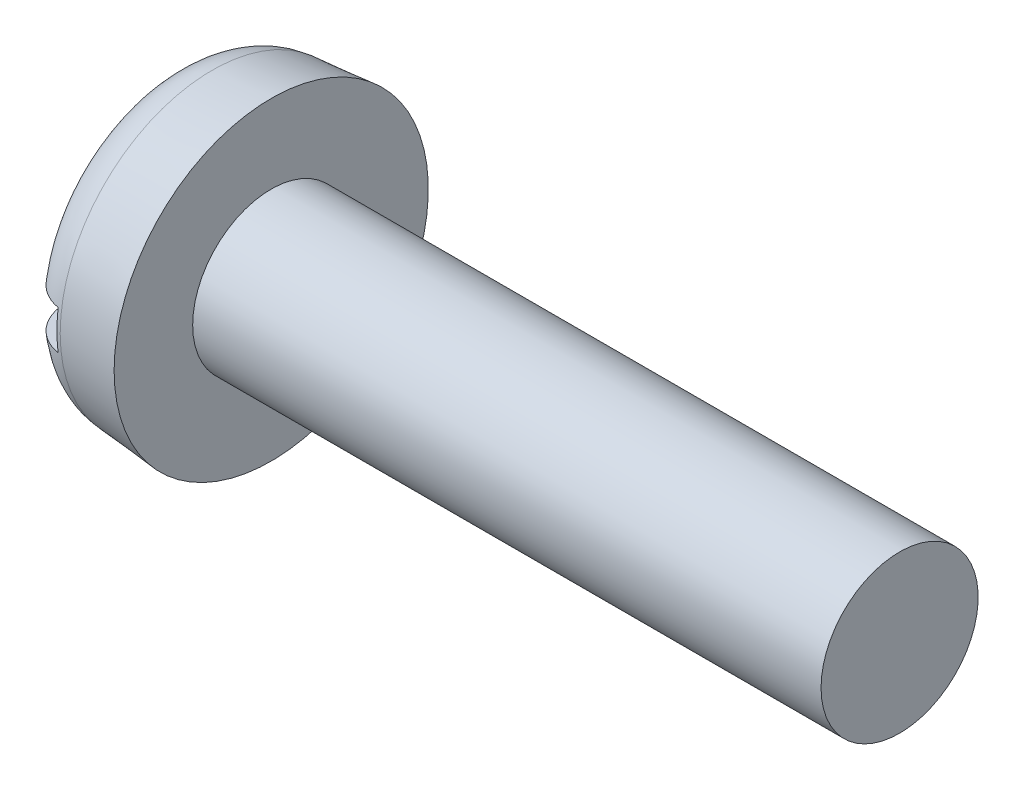
SolidWorks part; units mm, degrees
ref_plane "Plane1" through (0, 0, 0) normal (0, 0, 1) x (1, 0, 0)
ref_plane "Plane2" through (0, 0, 0) normal (0, 1, 0) x (1, 0, 0)
ref_plane "Plane3" through (0, 0, 0) normal (1, 0, 0) x (0, 0, -1)
sketch "BodySke" plane through (0, 0, 0) normal (0, 0, 1) x (1, 0, 0)
  line L0 (1.3, 1) -> (1.3, 2)
  line L1 (0, 0) -> (0, 1.8863)
  line L2 (-25.4, 0) -> (127, 0) construction
  line L3 (9.3, 0) -> (0, 0)
  line L4 (1.3, 1) -> (9.3, 1)
  line L5 (9.3, 1) -> (9.3, 0)
  line L6 (0, 1.8863) -> (1.3, 2)
  line L9 (1.7, 2.5875) -> (1.7, -6.9375) construction
  line L10 (1.3, 6.35) -> (1.3, -3.175) construction
  dimension "Length" = 8
  dimension "Head_ht" = 1.3
  dimension "Advance" = 0.4
  dimension "Thread_nom" = 8
  dimension "Head_dia" = 4
  dimension "Head_side_angle" = 5
  dimension "Diameter" = 2
revolve "Base-Revolve" add sketch "BodySke"
cosmetic thread "ThreadCosmetic" [suppressed]
fillet "Fillet1" [suppressed] radius 0.1
fillet "Fillet2" radius 0.6 1 edges at (0, 0, 1.8863)
sketch "Sketch2" plane through (0, 0, 0) normal (1, 0, 0) x (0, 0, -1)
  line L0 (2, -0.25) -> (-2, -0.25)
  line L1 (2, -0.25) -> (2, 0.25)
  line L2 (-2, 0.25) -> (2, 0.25)
  line L3 (-2, 0.25) -> (-2, -0.25)
  dimension "D1" = 4
  dimension "Slot_width" = 0.5
  dimension "D2" = 2
  dimension "D3" = 0.25
extrude "Slot" cut sketch "Sketch2" along normal blind 0.5
sketch "ThdSchSke" plane through (0, 0, 0) normal (0, 0, 1) x (1, 0, 0)
  line L0 (2.1, -0.774) -> (1.9418, -1)
  line L1 (2.1, -0.774) -> (2.2582, -1)
  line L2 (2.2582, -1) -> (2.2582, -1.25)
  line L3 (-3.175, 0) -> (5.1513, 0) construction
  line L5 (2.2582, -1.25) -> (1.9418, -1.25)
  line L6 (1.9418, -1.25) -> (1.9418, -1)
  dimension "Diameter" = 2
  dimension "SideAngle" = 55
  dimension "VeeAngle" = 70
  dimension "Thread_minor" = 1.548
  dimension "Overcut" = 2.5
  dimension "Start" = 2.1
revolve "ThreadSchematic" [suppressed] cut sketch "ThdSchSke" angle 360 about L3
pattern_linear "ThdSchPat" [suppressed]
equation "\"D1@Sketch2\" = \"Head_dia@BodySke\""
equation "\"D2@Sketch2\" = \"D1@Sketch2\" / 2"
equation "\"D3@Sketch2\" = \"Slot_width@Sketch2\" / 2"
equation "\"Thread_length@ThreadCosmetic\" = ((sgn( (\"Length@BodySke\" - \"Advance@BodySke\" * 2.0 ) - \"Thread_nom@BodySke\" )-1)*( (\"Length@BodySke\" - \"Advance@BodySke\"  * 2.0) - \"Thread_nom@BodySke\" ))/-2+ \"Thread_nom@BodySke\""
equation "\"Thread_minor@ThdSchSke\" = \"Thread_minor@ThreadCosmetic\""
equation "\"Diameter@ThdSchSke\" = \"Diameter@BodySke\""
equation "\"Overcut@ThdSchSke\" = \"Diameter@BodySke\" * 1.25"
equation "\"Start@ThdSchSke\" = \"Head_ht@BodySke\" + \"Length@BodySke\" - \"Thread_length@ThreadCosmetic\"  '---Non-countersunk---"
equation "\"Num_threads@ThdSchPat\" = int( \"Thread_length@ThreadCosmetic\" / \"Advance@BodySke\" + 0.999 )  + 1"
equation "\"Advance@ThdSchPat\" = \"Thread_length@ThreadCosmetic\" /  (\"Num_threads@ThdSchPat\" - 1) 'relax it"
